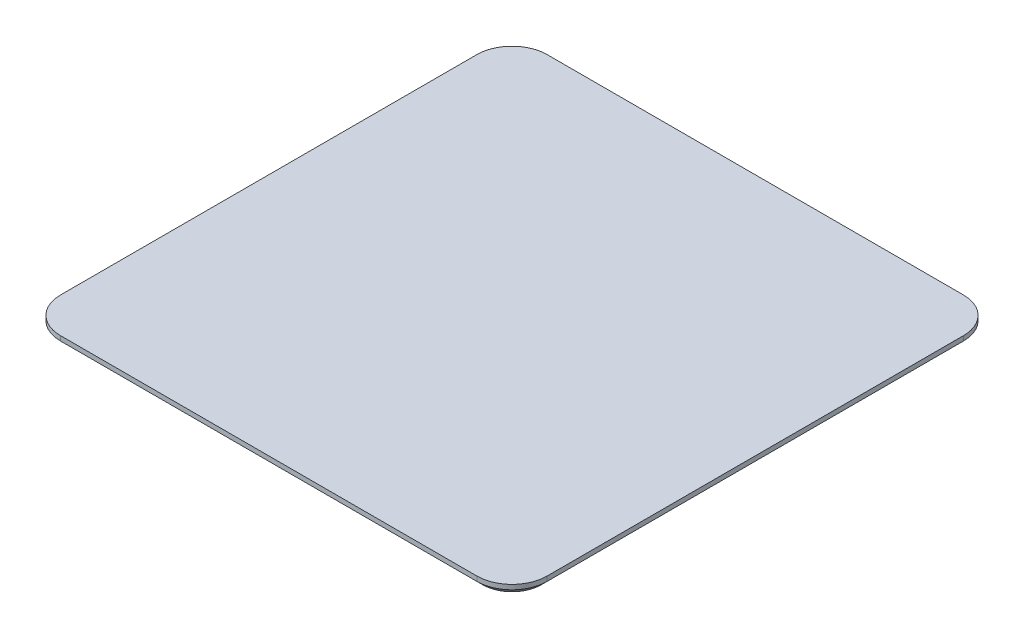
SolidWorks part; units mm, degrees
ref_plane "Спереди" through (0, 0, 0) normal (0, 0, 1) x (1, 0, 0)
ref_plane "Сверху" through (0, 0, 0) normal (0, 1, 0) x (1, 0, 0)
ref_plane "Справа" through (0, 0, 0) normal (1, 0, 0) x (0, 0, -1)
sketch "Эскиз1" plane through (0, 0, 0) normal (0, 1, 0) x (1, 0, 0)
  line L1 (-20.75, -20.75) -> (20.75, -20.75)
  line L2 (-20.75, -20.75) -> (-20.75, 20.75)
  line L3 (-20.75, 20.75) -> (20.75, 20.75)
  line L4 (20.75, -20.75) -> (20.75, 20.75)
  line L5 (0, 20.75) -> (0, -20.75) construction
  line L6 (-20.75, 0) -> (20.75, 0) construction
  point P0 (0, 0)
  dimension "D1" = 41.5
extrude "Бобышка-Вытянуть1" add sketch "Эскиз1" along normal blind 0.9
fillet "Скругление1" radius 3 4 edges at (-20.75, 0.45, -20.75) (-20.75, 0.45, 20.75) (20.75, 0.45, -20.75) (20.75, 0.45, 20.75)
chamfer "Фаска1" distance 0.5 angle 45 8 edges at (20.75, 0, 0) (19.8713, 0, -19.8713) (19.8713, 0, 19.8713) (0, 0, -20.75) (0, 0, 20.75) (-19.8713, 0, -19.8713) (-19.8713, 0, 19.8713) (-20.75, 0, 0)
